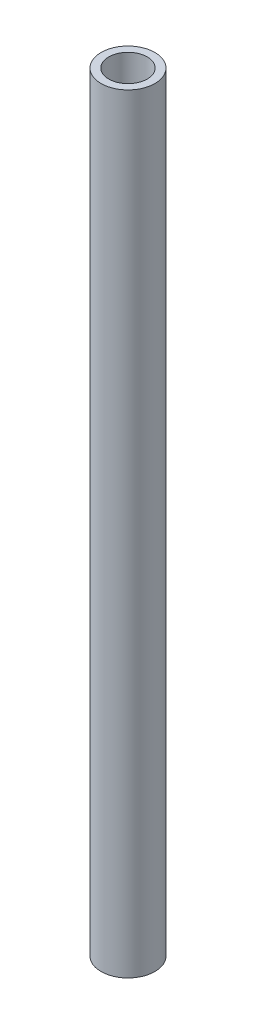
SolidWorks part; units mm, degrees
ref_plane "Front Plane" through (0, 0, 0) normal (0, 0, 1) x (1, 0, 0)
ref_plane "Top Plane" through (0, 0, 0) normal (0, 1, 0) x (1, 0, 0)
ref_plane "Right Plane" through (0, 0, 0) normal (1, 0, 0) x (0, 0, -1)
sketch "Sketch1" plane through (0, 0, 0) normal (0, 1, 0) x (1, 0, 0)
  circle A0 centre (0, 0) radius 13.335
  circle A1 centre (0, 0) radius 9.525
  dimension "D1" = 26.67
  dimension "D2" = 19.05
extrude "Boss-Extrude1" add sketch "Sketch1" along normal blind 381
